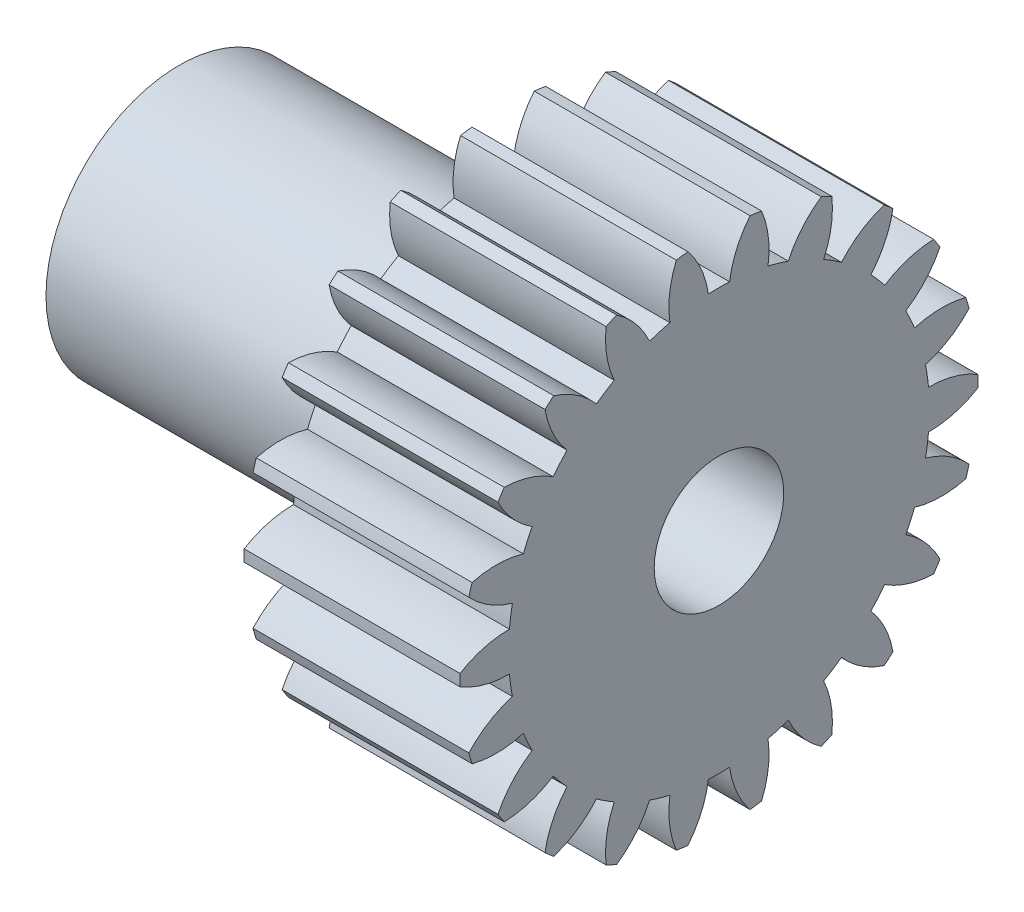
SolidWorks part; units mm, degrees
ref_plane "Plane1" through (0, 0, 0) normal (0, 0, 1) x (1, 0, 0)
ref_plane "Plane2" through (0, 0, 0) normal (0, 1, 0) x (1, 0, 0)
ref_plane "Plane3" through (0, 0, 0) normal (1, 0, 0) x (0, 0, -1)
sketch "HoldingSke" plane through (0, 0, 0) normal (0, 1, 0) x (1, 0, 0)
  line L0 (0, 0) -> (0.9272, -0.3746)
  line L1 (-15, 0) -> (100, 0) construction
  line L2 (0, 0) -> (-2.1039, 2.3779)
  line L3 (0, 0) -> (-11.863, 4.5341)
  line L4 (0, 0) -> (8.0072, 3.2351)
  line L5 (0, 0) -> (-23.4238, -8.7364)
  line L6 (0, 0) -> (-8.2896, -5.593)
  line L7 (-2.1039, 2.3779) -> (3.2774, 26.7919)
  line L8 (-76.2, 54.61) -> (-75.2, 54.61)
  line L9 (-71.009, 38.7566) -> (-53.1078, 45.2721)
  line L10 (-76.2, 71.12) -> (104.1128, 71.12)
  line L11 (0, 0) -> (-10, 0)
  line L12 (-76.2, 101.6) -> (-76.162, 101.6)
  line L13 (24.9733, 27.94) -> (52.9518, 28.4284)
  line L14 (24.9733, 27.94) -> (24.9743, 27.94)
  line L15 (24.9733, 27.94) -> (100.4006, 29.5858)
  line L16 (-63.627, -1) -> (-12.827, -1)
  circle A0 centre (0, 0) radius 3
  circle A1 centre (0, 0) radius 6.175
  circle A2 centre (0, 0) radius 6.175
  circle A3 centre (0, 0) radius 3
  dimension "MHD" = 12.35
  dimension "Hub_dia" = 12.35
  dimension "Bore" = 6
  dimension "MBD" = 6
  dimension "Num_teeth" = 22
  dimension "Pitch" = 1
  dimension "Overall_len" = 25
  dimension "Show_teeth" = 22
  dimension "Thickness" = 10
  dimension "OAL" = 25.0001
  dimension "T_dim" = 1
  dimension "Ap" = 20
  dimension "H" = 19.05
  dimension "Pitch_radius" = 180.3128
  dimension "Width" = 10
  dimension "Backlash" = 0.038
  dimension "Addendum_fac" = 1
  dimension "Dedendum_fac" = 1.25
  dimension "Clearance_fac" = 0.25
  dimension "Dedendum_add" = 0.001
  dimension "Module" = 1
sketch "BasProSke" plane through (0, 0, 0) normal (0, 1, 0) x (1, 0, 0)
  line L0 (-10, 0) -> (60, 0) construction
  line L1 (0, 0) -> (0, 12)
  line L2 (0, 0) -> (10, 0)
  line L3 (10, 0) -> (10, 12)
  line L4 (10, 12) -> (0, 12)
  dimension "Thickness" = 10
  dimension "Diameter" = 24
revolve "Base-Revolve" add sketch "BasProSke" angle 360 about L0
sketch "TooCutSke" plane through (0, 0, 0) normal (1, 0, 0) x (0, 0, -1)
  line L1 (0, 0) -> (0, 107) construction
  line L2 (0, 0) -> (-0.8512, 10.967) construction
  line L3 (0, 0) -> (-3.1242, 21.7296) construction
  line L4 (-0.8512, 10.967) -> (-1.5621, 10.8648) construction
  arc A0 (0.491, 9.7366) -> (-0.491, 9.7366) centre (0, 0) ccw
  arc A1 (1.4609, 11.9363) -> (-1.4609, 11.9363) centre (0, 0) ccw
  circle A2 centre (0, 0) radius 11 construction
  circle A3 centre (0, 0) radius 10.3366 construction
  arc A4 (-0.491, 9.7366) -> (-1.4609, 11.9363) centre (-4.8488, 9.1288) ccw
  arc A5 (1.4609, 11.9363) -> (0.491, 9.7366) centre (4.8488, 9.1288) ccw
  dimension "Root_dia" = 19.498
  dimension "Overcut_dia" = 24.0508
  dimension "Pitch_dia" = 22
  dimension "Base_dia" = 20.6732
  dimension "Flank_rad" = 4.4
  dimension "Half_ang" = 8.182
  dimension "Half_CT" = 0.7182
extrude "ToothCut" cut sketch "TooCutSke" along normal through all
fillet "Breaks" [suppressed] radius 0.02
fillet "RootFillets" [suppressed] radius 0.251
pattern_circular "TeethCuts" count 22 every 16.364 about axis through (-10, 0, 0) along (1, 0, 0) of "ToothCut", "RootFillets", "Breaks"
sketch "HubNeaOneSke" plane through (0, 0, 0) normal (-1, 0, 0) x (0, 0, 1)
  circle A0 centre (0, 0) radius 6.175
  dimension "Diameter" = 12.35
extrude "HubNearOne" add sketch "HubNeaOneSke" along normal blind 15.0001
sketch "HubNeaBotSke" plane through (0, 0, 0) normal (-1, 0, 0) x (0, 0, 1)
  circle A0 centre (0, 0) radius 6.175
  dimension "Diameter" = 12.35
extrude "HubNearBoth" [suppressed] add sketch "HubNeaBotSke" along normal blind 7.5
ref_plane "FarPln" through (10, 0, 0) normal (1, 0, 0) x (0, 0, -1)
sketch "HubFarSke" plane through (10, 0, 0) normal (1, 0, 0) x (0, 0, -1)
  circle A0 centre (0, 0) radius 6.175
  dimension "Diameter" = 12.35
extrude "HubFar" [suppressed] add sketch "HubFarSke" along normal blind 7.5
sketch "BorSke" plane through (0, 0, 0) normal (1, 0, 0) x (0, 0, -1)
  circle A0 centre (0, 0) radius 3
  dimension "Diameter" = 6
extrude "Bore" cut sketch "BorSke" along normal mid plane 50.0001
sketch "KeySke" plane through (0, 0, 0) normal (1, 0, 0) x (0, 0, -1)
  line L0 (-1, 0) -> (-1, 4)
  line L1 (-1, 4) -> (1, 4)
  line L2 (1, 4) -> (1, 0)
  line L3 (0, 0) -> (0, 34) construction
  line L4 (-1, 0) -> (1, 0)
  dimension "Offset" = 4
  dimension "Width" = 2
extrude "Keyway" [suppressed] cut sketch "KeySke" along normal mid plane 50.0001
pattern_circular "Keyway2" [suppressed] count 2 every 90 about axis through (-10, 0, 0) along (1, 0, 0)
sketch "Sketch1" plane through (0, 0, 0) normal (0, 1, 0) x (1, 0, 0)
  line L0 (35, 0) -> (-35, 0) construction
  point P5 (0, 0)
  dimension "D1" = 70
equation "' \"Module@HoldingSke\" = 6.35"
equation "' \"Num_teeth@HoldingSke\" = 12"
equation "' \"Ap@HoldingSke\" =  20"
equation "' \"Ap@HoldingSke\" = 20"
equation "' \"Width@HoldingSke\" = 0.5 * 25.4"
equation "' \"Hub_dia@HoldingSke\"= 1 * 25.4"
equation "' \"Hub_dia@HoldingSke\" = 1 * 25.4"
equation "' \"Overall_len@HoldingSke\" = 1.0 * 25.4"
equation "' \"Bore@HoldingSke\" = 0.75 * 25.4"
equation "' \"T_dim@HoldingSke\" = 0.1 * 25.4"
equation "' \"Width@KeySke\" = 0.25 * 25.4"
equation "' \"Show_teeth@HoldingSke\" = 13"
equation "' \"Backlash@HoldingSke\" = 0.009 * 25.4"
equation "' \"Addendum_fac@HoldingSke\" = 1.0"
equation "' \"Dedendum_fac@HoldingSke\" = 1.25"
equation "' \"Dedendum_add@HoldingSke\" = 0.00005 * 25.4"
equation "' \"Clearance_fac@HoldingSke\" = 0.25"
equation "\"Pitch@HoldingSke\" = 1 / \"Module@HoldingSke\""
equation "\"Overcut_dia@TooCutSke\" = (\"Num_teeth@HoldingSke\" + 2 * \"Addendum_fac@HoldingSke\") / \"Pitch@HoldingSke\" + 0.002 * 25.4"
equation "\"Pitch_dia@TooCutSke\" = \"Num_teeth@HoldingSke\" / \"Pitch@HoldingSke\""
equation "\"Base_dia@TooCutSke\" = \"Num_teeth@HoldingSke\" / \"Pitch@HoldingSke\" * cos((\"Ap@HoldingSke\"  * 3.14159265 / 180))"
equation "\"Root_dia@TooCutSke\" = (\"Num_teeth@HoldingSke\" + 2) / \"Pitch@HoldingSke\" - 2 * (\"Addendum_fac@HoldingSke\" + \"Dedendum_fac@HoldingSke\") / \"Pitch@HoldingSke\" - \"Dedendum_add@HoldingSke\" * 2"
equation "\"Half_ang@TooCutSke\" = 180 / \"Num_teeth@HoldingSke\""
equation "\"Half_CT@TooCutSke\" = \"Num_teeth@HoldingSke\" / \"Pitch@HoldingSke\" * sin((3.14159265 / 2 / \"Num_teeth@HoldingSke\")) / 2 - 7 * \"Backlash@HoldingSke\" / 4"
equation "\"Flank_rad@TooCutSke\" = \"Num_teeth@HoldingSke\" / \"Pitch@HoldingSke\" / 5"
equation "\"Radius@RootFillets\" = \"Clearance_fac@HoldingSke\" / \"Pitch@HoldingSke\" + \"Dedendum_add@HoldingSke\""
equation "\"Break_rad@Breaks\" = 0.02 / \"Pitch@HoldingSke\""
equation "\"Thickness@HoldingSke\" = \"Width@HoldingSke\""
equation "\"OAL@HoldingSke\" = \"Thickness@HoldingSke\""
equation "\"MHD@HoldingSke\" = (\"Num_teeth@HoldingSke\" + 2) / \"Pitch@HoldingSke\" - 2 * (\"Addendum_fac@HoldingSke\" + \"Dedendum_fac@HoldingSke\")  / \"Pitch@HoldingSke\" - \"Dedendum_add@HoldingSke\" * 2"
equation "\"MBD@HoldingSke\" = (\"Num_teeth@HoldingSke\" + 2) / \"Pitch@HoldingSke\" - 2 * (\"Addendum_fac@HoldingSke\" + \"Dedendum_fac@HoldingSke\")  / \"Pitch@HoldingSke\" - \"Dedendum_add@HoldingSke\" * 2 - 0.002 * 25.4"
equation "\"MHD@HoldingSke\" = ((sgn( \"MHD@HoldingSke\" - \"Hub_dia@HoldingSke\" )-1)*( \"MHD@HoldingSke\" - \"Hub_dia@HoldingSke\" ))/-2+ \"Hub_dia@HoldingSke\""
equation "\"MBD@HoldingSke\" = ((sgn( \"MBD@HoldingSke\" - \"Bore@HoldingSke\" )-1)*( \"MBD@HoldingSke\" - \"Bore@HoldingSke\" ))/-2+ \"Bore@HoldingSke\""
equation "\"OAL@HoldingSke\" = ((sgn( \"OAL@HoldingSke\" - \"Overall_len@HoldingSke\" )+1)*( \"OAL@HoldingSke\" - \"Overall_len@HoldingSke\" ))/2 + \"Overall_len@HoldingSke\" + 0.000002 * 25.4"
equation "\"Num_teeth@TeethCuts\" = int( \"Show_teeth@HoldingSke\" ) + 1"
equation "\"Num_teeth@TeethCuts\" = ((sgn( \"Num_teeth@TeethCuts\" - \"Num_teeth@HoldingSke\" )-1)*( \"Num_teeth@TeethCuts\" - \"Num_teeth@HoldingSke\" ))/-2+ \"Num_teeth@HoldingSke\""
equation "\"Num_teeth@TeethCuts\" = ((sgn( \"Num_teeth@TeethCuts\" - 2.0)+1)*( \"Num_teeth@TeethCuts\" - 2.0))/2 +2.0"
equation "\"Angle@TeethCuts\" = 360.0 / \"Num_teeth@HoldingSke\""
equation "\"Diameter@BasProSke\" = (\"Num_teeth@HoldingSke\" + 2 * \"Addendum_fac@HoldingSke\") / \"Pitch@HoldingSke\""
equation "\"Thickness@BasProSke\"  = \"Thickness@HoldingSke\""
equation "' \"Fillet_rad@BasProSke\" =  \"Thickness@HoldingSke\" * 0.05"
equation "' \"Fillet_rad@BasProSke\" = \"Thickness@HoldingSke\" * 0.05"
equation "\"MHD@HoldingSke\" = ((sgn( \"MHD@HoldingSke\" - \"Root_dia@TooCutSke\" )-1)*( \"MHD@HoldingSke\" - \"Root_dia@TooCutSke\" ))/-2+ \"Root_dia@TooCutSke\""
equation "\"Diameter@HubNeaOneSke\" = \"MHD@HoldingSke\""
equation "\"Length@HubNearOne\" = \"OAL@HoldingSke\" - \"Thickness@BasProSke\""
equation "\"Diameter@HubNeaBotSke\" = \"MHD@HoldingSke\""
equation "\"Length@HubNearBoth\" = ( \"OAL@HoldingSke\" - \"Thickness@BasProSke\" ) / 2.0"
equation "\"Thickness@FarPln\" = \"Thickness@BasProSke\""
equation "\"Diameter@HubFarSke\" = \"MHD@HoldingSke\""
equation "\"Length@HubFar\" = ( \"OAL@HoldingSke\" - \"Thickness@BasProSke\" ) / 2.0"
equation "\"Diameter@BorSke\" = \"MBD@HoldingSke\""
equation "\"D1@Bore\" = \"OAL@HoldingSke\" * 2.0"
equation "\"D1@Keyway\" = \"OAL@HoldingSke\" * 2.0"
equation "\"Offset@KeySke\" = \"T_dim@HoldingSke\" + \"MBD@HoldingSke\" / 2.0"
